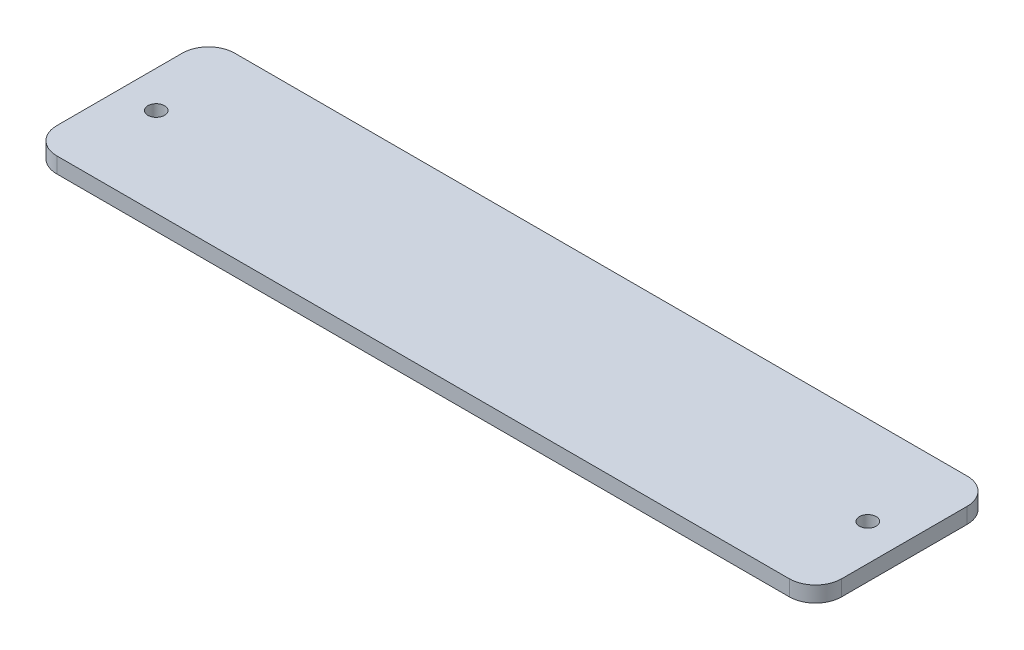
SolidWorks part; units mm, degrees
ref_plane "正面" through (0, 0, 0) normal (0, 0, 1) x (1, 0, 0)
ref_plane "平面" through (0, 0, 0) normal (0, 1, 0) x (1, 0, 0)
ref_plane "右側面" through (0, 0, 0) normal (1, 0, 0) x (0, 0, -1)
sketch "ｽｹｯﾁ1" plane through (0, 0, 0) normal (0, 1, 0) x (1, 0, 0)
  line L1 (0, 8) -> (150, 8)
  line L3 (0, 42) -> (150, 42)
  line L84 (75, 0) -> (75, 50) construction
  line L167 (150, 42) -> (150, 8)
  line L391 (0, 42) -> (0, 8)
  circle A0 centre (143, 25) radius 3 construction
  circle A1 centre (143, 25) radius 1.6
  circle A12 centre (7, 25) radius 1.6
  circle A14 centre (7, 25) radius 3 construction
extrude "ﾎﾞｽ - 押し出し1" add sketch "ｽｹｯﾁ1" along normal blind 3
fillet "ﾌｨﾚｯﾄ1" radius 5 4 edges at (150, 1.5, -8) (0, 1.5, -8) (150, 1.5, -42) (0, 1.5, -42)
